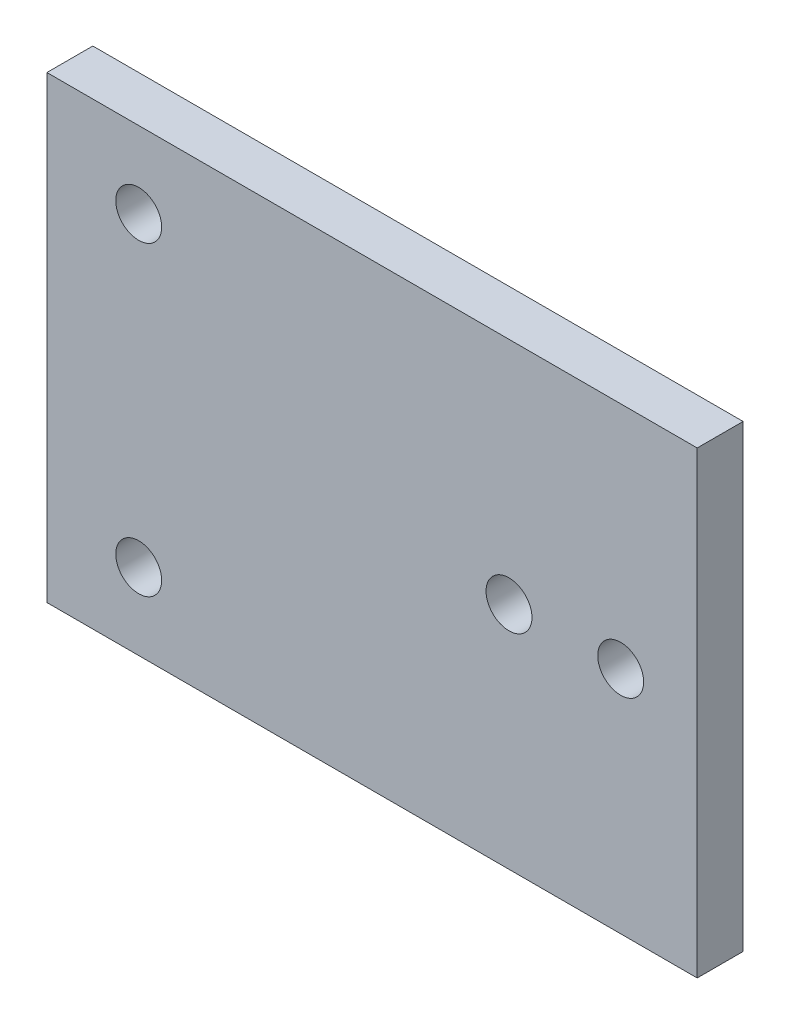
SolidWorks part; units mm, degrees
ref_plane "Alzado" through (0, 0, 0) normal (0, 0, 1) x (1, 0, 0)
ref_plane "Planta" through (0, 0, 0) normal (0, 1, 0) x (1, 0, 0)
ref_plane "Vista lateral" through (0, 0, 0) normal (1, 0, 0) x (0, 0, -1)
sketch "Croquis1" plane through (0, 0, 0) normal (0, 0, 1) x (1, 0, 0)
  line L0 (0, 15) -> (6, 15) construction
  line L1 (0, 0) -> (42.5, 0)
  line L2 (0, 0) -> (0, 30)
  line L3 (0, 30) -> (42.5, 30)
  line L4 (42.5, 0) -> (42.5, 30)
  line L5 (6, 15) -> (20, 15) construction
  line L6 (20, 15) -> (22.5, 15) construction
  line L7 (22.5, 15) -> (37.5, 15) construction
  line L8 (37.5, 15) -> (42.5, 15) construction
  line L9 (6, 5) -> (6, 25) construction
  circle A0 centre (6, 25) radius 1.5
  circle A1 centre (6, 5) radius 1.5
  circle A4 centre (37.5, 15) radius 1.5
  circle A5 centre (30.2, 15) radius 1.5
  dimension "D8" = 3
  dimension "D9" = 7.3
  dimension "D1" = 42.5
  dimension "D2" = 30
  dimension "D3" = 6
  dimension "D4" = 14
  dimension "D5" = 2.5
  dimension "D6" = 15
  dimension "D7" = 10
extrude "Saliente-Extruir1" add sketch "Croquis1" along normal blind 3
